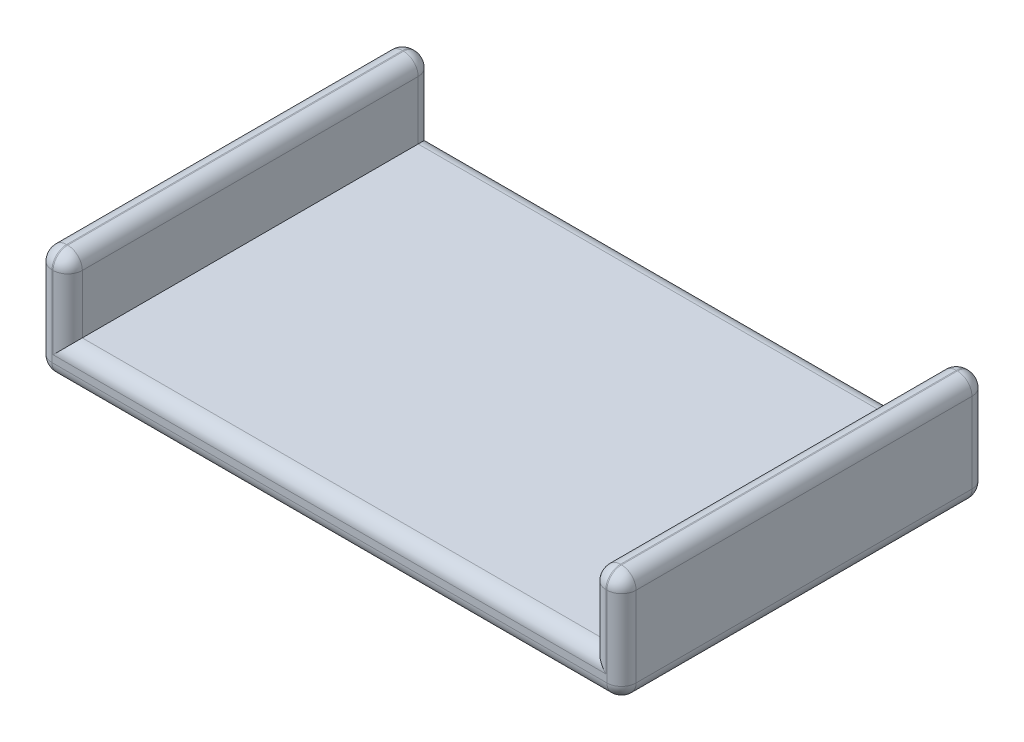
SolidWorks part; units mm, degrees
ref_plane "前视基准面" through (0, 0, 0) normal (0, 0, 1) x (1, 0, 0)
ref_plane "上视基准面" through (0, 0, 0) normal (0, 1, 0) x (1, 0, 0)
ref_plane "右视基准面" through (0, 0, 0) normal (1, 0, 0) x (0, 0, -1)
sketch "Sketch1" plane through (0, 0, 0) normal (0, 1, 0) x (1, 0, 0)
  line L1 (-40, -25) -> (40, -25)
  line L2 (-40, -25) -> (-40, 25)
  line L3 (-40, 25) -> (40, 25)
  line L4 (40, -25) -> (40, 25)
  line L5 (-40, -25) -> (40, 25) construction
  line L6 (-40, 25) -> (40, -25) construction
  point P0 (0, 0)
  dimension "D1" = 80
  dimension "D2" = 50
extrude "Boss-Extrude1" add sketch "Sketch1" along normal blind 5
sketch "Sketch2" plane through (0, 0, 0) normal (0, -1, 0) x (1, 0, 0)
  line L0 (-20.9, 0) -> (20.9, 0) construction
  circle A0 centre (-20.9, 0) radius 7.9
  circle A1 centre (20.9, 0) radius 7.9
  point P4 (-13, 0)
  point P5 (13, 0)
  dimension "D2" = 15.8
  dimension "D1" = 26
extrude "Boss-Extrude2" add sketch "Sketch2" along normal blind 5
sketch "Sketch3" plane through (0, 5, 0) normal (0, 1, 0) x (1, 0, 0)
  line L1 (-35.85, -25) -> (35.85, -25)
  line L2 (-35.85, -25) -> (-35.85, 25)
  line L3 (-35.85, 25) -> (35.85, 25)
  line L4 (40, -25) -> (40, 25)
  line L5 (40, 25) -> (-40, 25)
  line L6 (-40, 25) -> (-40, -25)
  line L7 (-40, -25) -> (40, -25)
  line L8 (40, -25) -> (40, 25)
  line L9 (40, 25) -> (-40, 25)
  line L10 (-40, 25) -> (-40, -25)
  line L11 (-40, -25) -> (40, -25)
  line L12 (35.85, -25) -> (35.85, 25)
  line L13 (-35.85, -25) -> (35.85, 25) construction
  line L14 (-35.85, 25) -> (35.85, -25) construction
  point P2 (0, 0)
  line M9 (40, -25) -> (40, 25)
  line M10 (40, 25) -> (-40, 25)
  line M11 (-40, 25) -> (-40, -25)
  line M12 (-40, -25) -> (40, -25)
  dimension "D2" = 71.7
  dimension "D1" = 0
extrude "Boss-Extrude3" add sketch "Sketch3" along normal blind 10 contours L2 M12 M10 M11 | L12 M12 M9 M10
fillet "Fillet1" radius 2 2 edges at (20.9, -5, -7.9) (-20.9, -5, -7.9)
fillet "Fillet2" radius 2 22 edges at (35.85, 10, 25) (35.85, 10, -25) (0, 5, -25) (-35.85, 10, -25) (-35.85, 10, 25) (0, 0, -25) (0, 5, 25) (0, 0, 25) (40, 7.5, 25) (40, 7.5, -25) (40, 0, 0) (-40, 7.5, -25) (-40, 7.5, 25) (-40, 0, 0) (-35.85, 15, 0) (-40, 15, 0) (-37.925, 15, 25) (-37.925, 15, -25) (37.925, 15, 25) (37.925, 15, -25) (35.85, 15, 0) (40, 15, 0)
